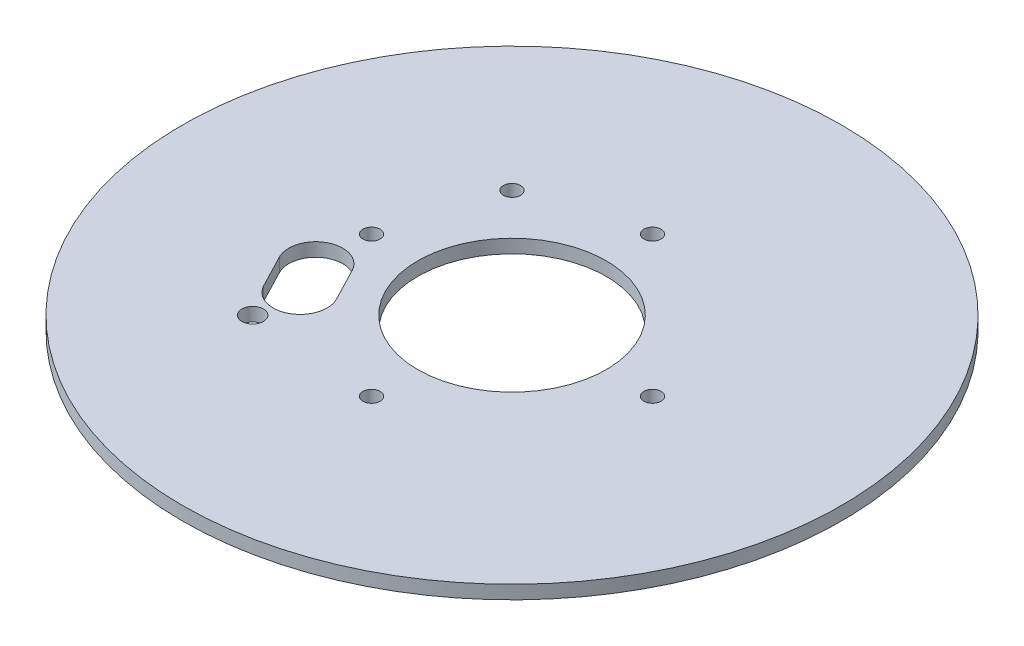
SolidWorks part; units mm, degrees
material "Acrylic (Medium-high impact)"
ref_plane "Front" through (0, 0, 0) normal (0, 0, 1) x (1, 0, 0)
ref_plane "Top" through (0, 0, 0) normal (0, 1, 0) x (1, 0, 0)
ref_plane "Right" through (0, 0, 0) normal (1, 0, 0) x (0, 0, -1)
sketch "Sketch1" plane through (0, 0, 0) normal (0, 1, 0) x (1, 0, 0)
  circle A0 centre (0, 0) radius 77.46
  dimension "D1" = 154.92
extrude "Boss-Extrude1" add sketch "Sketch1" along normal blind 3.175
sketch "Sketch24" plane through (0, 3.175, 0) normal (0, 1, 0) x (1, 0, 0)
  line L0 (-33.5359, -12.5897) -> (-29.5483, -20.2499) construction
  line L1 (-27.9034, -9.6576) -> (-23.9158, -17.3178)
  line L2 (-39.1685, -15.5218) -> (-35.1808, -23.182)
  line L3 (-33.5359, -12.5897) -> (0, 0) construction
  line L4 (0, 0) -> (-29.5483, -20.2499) construction
  line L5 (-31.5421, -16.4198) -> (0, 0) construction
  line L6 (0, 0) -> (33.02, 0) construction
  circle A0 centre (0, 0) radius 22.1615
  circle A1 centre (0, 0) radius 33.02 construction
  circle A2 centre (0, 33.02) radius 2.0193
  circle A3 centre (33.02, 0) radius 2.0193
  circle A4 centre (-33.02, 0) radius 2.0193
  circle A5 centre (0, -33.02) radius 2.0193
  circle A6 centre (-30.48, -30.48) radius 2.54
  circle A7 centre (-25.4, 25.4) radius 2.0193
  arc A8 (-27.9034, -9.6576) -> (-39.1685, -15.5218) centre (-33.5359, -12.5897) ccw
  arc A9 (-35.1808, -23.182) -> (-23.9158, -17.3178) centre (-29.5483, -20.2499) ccw
  point P18 (-31.5421, -16.4198)
  dimension "D1" = 4.0386
  dimension "D2" = 5.08
  dimension "D3" = 44.323
  dimension "D10" = 6.35
  dimension "D4" = 33.02
  dimension "D5" = 25.4
  dimension "D6" = 25.4
  dimension "D7" = 30.48
  dimension "D8" = 30.48
  dimension "D9" = 8.636
  dimension "D11" = 35.56
  dimension "D12" = 27.5
extrude "Cut-Extrude14" cut sketch "Sketch24" against normal through all
